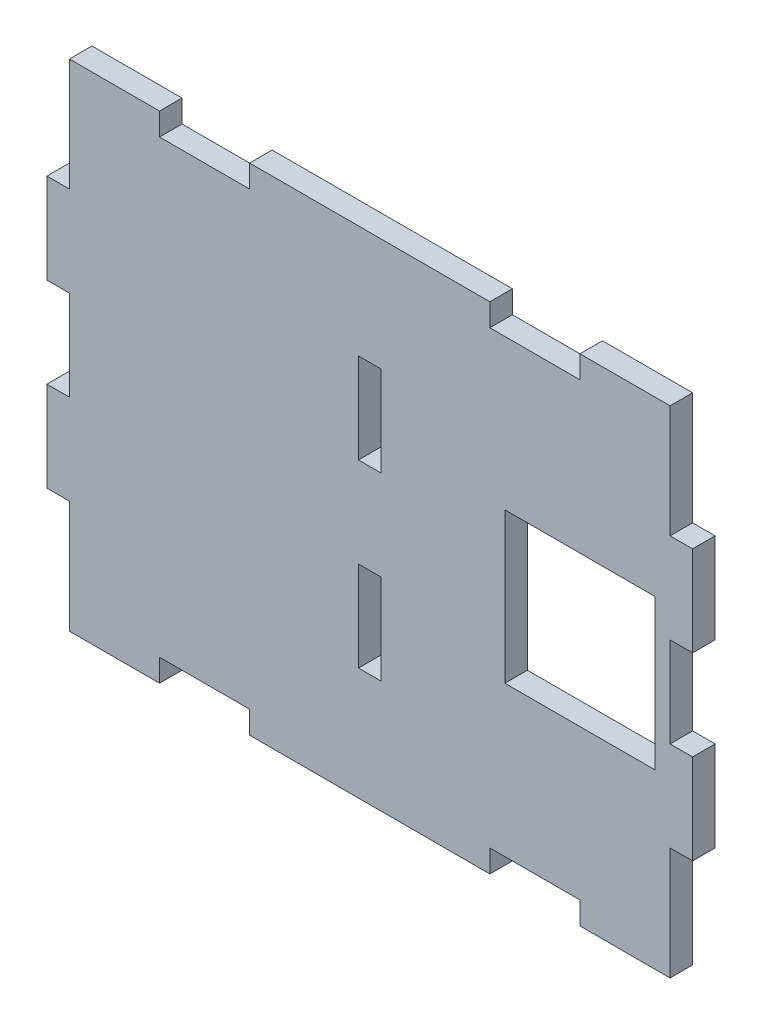
SolidWorks part; units mm, degrees
material "Pinho"
ref_plane "Plano frontal" through (0, 0, 0) normal (0, 0, 1) x (1, 0, 0)
ref_plane "Plano superior" through (0, 0, 0) normal (0, 1, 0) x (1, 0, 0)
ref_plane "Plano direito" through (0, 0, 0) normal (1, 0, 0) x (0, 0, -1)
sketch "Esboço1" plane through (0, 0, 0) normal (0, 0, 1) x (1, 0, 0)
  line L0 (-31.2169, 10.5171) -> (-31.2169, -1.4829)
  line L1 (-19.2169, 34.5171) -> (-7.2169, 34.5171)
  line L2 (-31.2169, 34.5171) -> (-31.2169, 22.5171)
  line L3 (-19.2169, -25.4829) -> (-7.2169, -25.4829)
  line L4 (48.7831, 34.5171) -> (48.7831, 22.5171)
  line L5 (-31.2169, -13.4829) -> (-31.2169, -25.4829)
  line L6 (-31.2169, 10.5171) -> (-34.2169, 10.5171)
  line L9 (-31.2169, 22.5171) -> (-34.2169, 22.5171)
  line L10 (-34.2169, 10.5171) -> (-34.2169, 22.5171)
  line L12 (-31.2169, 34.5171) -> (-31.2169, 37.5171)
  line L13 (-34.2169, -13.4829) -> (-31.2169, -13.4829)
  line L14 (-34.2169, -13.4829) -> (-34.2169, -1.4829)
  line L15 (-34.2169, -1.4829) -> (-31.2169, -1.4829)
  line L17 (-31.2169, 37.5171) -> (-19.2169, 37.5171)
  line L18 (-19.2169, 34.5171) -> (-19.2169, 37.5171)
  line L20 (48.7831, 34.5171) -> (48.7831, 37.5171)
  line L21 (48.7831, 37.5171) -> (36.7831, 37.5171)
  line L22 (36.7831, 34.5171) -> (36.7831, 37.5171)
  line L24 (-7.2169, 34.5171) -> (-7.2169, 37.5171)
  line L25 (-7.2169, 37.5171) -> (-1.2169, 37.5171)
  line L27 (48.7831, -13.4829) -> (48.7831, -25.4829)
  line L28 (48.7831, 10.5171) -> (51.7831, 10.5171)
  line L30 (48.7831, 22.5171) -> (51.7831, 22.5171)
  line L31 (51.7831, 10.5171) -> (51.7831, 22.5171)
  line L32 (24.7831, -25.4829) -> (36.7831, -25.4829)
  line L34 (48.7831, -13.4829) -> (51.7831, -13.4829)
  line L36 (48.7831, -1.4829) -> (51.7831, -1.4829)
  line L37 (51.7831, -13.4829) -> (51.7831, -1.4829)
  line L38 (48.7831, 10.5171) -> (48.7831, -1.4829)
  line L39 (-31.2169, -25.4829) -> (-31.2169, -28.4829)
  line L40 (-31.2169, -28.4829) -> (-19.2169, -28.4829)
  line L41 (-19.2169, -25.4829) -> (-19.2169, -28.4829)
  line L43 (48.7831, -25.4829) -> (48.7831, -28.4829)
  line L44 (48.7831, -28.4829) -> (36.7831, -28.4829)
  line L45 (36.7831, -25.4829) -> (36.7831, -28.4829)
  line L47 (-7.2169, -25.4829) -> (-7.2169, -28.4829)
  line L48 (-7.2169, -28.4829) -> (4.7831, -28.4829)
  line L52 (7.2831, 22.5171) -> (10.2831, 22.5171)
  line L53 (7.2831, 22.5171) -> (7.2831, 10.5171)
  line L54 (7.2831, 10.5171) -> (10.2831, 10.5171)
  line L55 (10.2831, 22.5171) -> (10.2831, 10.5171)
  line L56 (7.2831, 22.5171) -> (10.2831, 10.5171) construction
  line L57 (7.2831, 10.5171) -> (10.2831, 22.5171) construction
  line L58 (7.2831, -1.4829) -> (10.2831, -1.4829)
  line L59 (7.2831, -1.4829) -> (7.2831, -13.4829)
  line L60 (7.2831, -13.4829) -> (10.2831, -13.4829)
  line L61 (10.2831, -1.4829) -> (10.2831, -13.4829)
  line L62 (7.2831, -1.4829) -> (10.2831, -13.4829) construction
  line L63 (7.2831, -13.4829) -> (10.2831, -1.4829) construction
  line L65 (26.7831, -5.4829) -> (46.7831, -5.4829)
  line L66 (26.7831, -5.4829) -> (26.7831, 14.5171)
  line L67 (26.7831, 14.5171) -> (46.7831, 14.5171)
  line L68 (46.7831, -5.4829) -> (46.7831, 14.5171)
  line L69 (26.7831, -5.4829) -> (46.7831, 14.5171) construction
  line L70 (26.7831, 14.5171) -> (46.7831, -5.4829) construction
  line L72 (24.7831, 37.5171) -> (24.7831, 34.5171)
  line L73 (24.7831, 34.5171) -> (36.7831, 34.5171)
  line L75 (24.7831, -25.4829) -> (24.7831, -28.4829)
  line L76 (24.7831, -28.4829) -> (4.7831, -28.4829)
  line L77 (-1.2169, 37.5171) -> (24.7831, 37.5171)
  point P0 (0, 0)
  point P22 (8.7831, 16.5171)
  point P49 (8.7831, -7.4829)
  point P56 (36.7831, 4.5171)
  dimension "D1" = 60
  dimension "D2" = 80
  dimension "D3" = 12
  dimension "D4" = 12
  dimension "D5" = 12
  dimension "D6" = 12
  dimension "D7" = 12
  dimension "D8" = 40
  dimension "D9" = 12
  dimension "D10" = 12
  dimension "D11" = 12
  dimension "D12" = 12
  dimension "D13" = 12
  dimension "D14" = 12
  dimension "D15" = 12
  dimension "D16" = 12
  dimension "D17" = 3
  dimension "D18" = 3
  dimension "D19" = 3
  dimension "D20" = 3
  dimension "D21" = 3
  dimension "D22" = 3
  dimension "D23" = 3
  dimension "D24" = 3
  dimension "D25" = 40
  dimension "D26" = 3
  dimension "D27" = 3
  dimension "D28" = 3
  dimension "D29" = 3
  dimension "D30" = 12
  dimension "D31" = 3
  dimension "D32" = 12
  dimension "D33" = 12
  dimension "D36" = 3
  dimension "D37" = 3
  dimension "D38" = 20
  dimension "D39" = 20
  dimension "D40" = 2
  dimension "D42" = 12
extrude "Ressalto-extrusão1" add sketch "Esboço1" along normal blind 3
